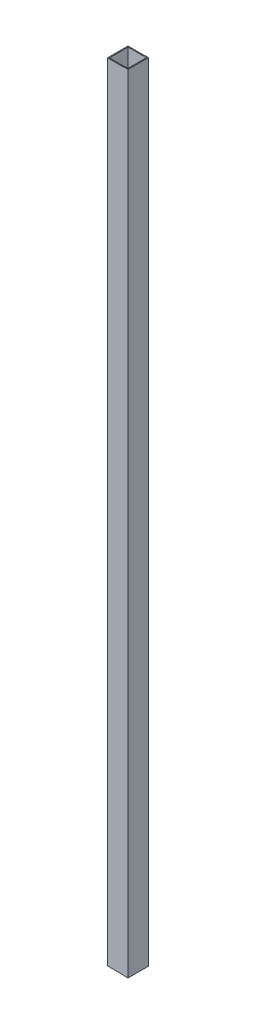
SolidWorks part; units mm, degrees
ref_plane "Front Plane" through (0, 0, 0) normal (0, 0, 1) x (1, 0, 0)
ref_plane "Top Plane" through (0, 0, 0) normal (0, 1, 0) x (1, 0, 0)
ref_plane "Right Plane" through (0, 0, 0) normal (1, 0, 0) x (0, 0, -1)
sketch "Sketch1" plane through (0, 0, 0) normal (0, 1, 0) x (1, 0, 0)
  line L0 (0, 0) -> (0, 50)
  line L1 (0, 50) -> (50, 50)
  line L2 (50, 50) -> (50, 0)
  line L3 (50, 0) -> (0, 0)
  line L4 (2.2, 47.8) -> (47.8, 47.8)
  line L5 (47.8, 47.8) -> (47.8, 2.2)
  line L6 (47.8, 2.2) -> (2.2, 2.2)
  line L7 (2.2, 2.2) -> (2.2, 47.8)
  dimension "D1" = 50
  dimension "D2" = 50
  dimension "D3" = 2.2
extrude "Boss-Extrude1" add sketch "Sketch1" along normal blind 1923
sketch "Sketch2" plane through (0, 0, 0) normal (0, 0, 1) x (1, 0, 0)
  line L0 (0, 0) -> (0, 0.5)
  line L1 (0, 1923) -> (0, 0) construction
  line L2 (0, 0.5) -> (40, 0.5)
  line L3 (40, 0.5) -> (40, 0)
  line L5 (40, 0) -> (0, 0)
  line L6 (0, 1923) -> (40, 1923)
  line L7 (0, 1923) -> (50, 1923) construction
  line L8 (40, 1923) -> (40, 1922.5)
  line L9 (40, 1922.5) -> (0, 1922.5)
  line L10 (0, 1922.5) -> (0, 1923)
  dimension "D1" = 0.5
  dimension "D2" = 40
  dimension "D3" = 0.5
  dimension "D4" = 40
extrude "Cut-Extrude2" cut sketch "Sketch2" against normal blind 50
equation "\"SquareTube_length\"=1923.0"
equation "\"D1@Boss-Extrude1\"=\"SquareTube_length\""
equation "\"SquareTube_inFront1_cutDepth50_R\"=0.5"
equation "\"D1@Sketch2\" = \"SquareTube_inFront3_cutDepth50_R\""
equation "\"SquareTube_inFront1_cutDepth50_L\"=0.5"
equation "\"D3@Sketch2\"= \"SquareTube_inFront3_cutDepth50_L\""
equation "\"CarBeamWidth\"=700.0"
equation "\"MetalSheet_3mm_length\"=5030.0"
equation "\"MetalSheet_3mm_width\"=1923.0"
equation "\"MetalSheet_3mm_FloorCut_L_length\"=1764.0"
equation "\"MetalSheet_3mm_FloorCut_L_disdance\"=1665.0"
equation "\"MetalSheet_3mm_FloorCut_R_length\"=1764.0"
equation "\"MetalSheet_3mm_FloorCut_R_disdance\"=1665.0"
equation "\"indoorHeight\"=1940.0"
equation "\"x\"=66.0"
equation "\"da\"=62.0"
equation "\"SquareTube_wheel_length\"= 750"
equation "\"channelSteel_length\"=5030.0"
equation "\"SquareTube_inFront2_cutDepth50_R\"=0.5"
equation "\"SquareTube_inFront2_cutDepth50_L\"=0.5"
equation "\"SquareTube_inFront3_cutDepth50_R\"=0.5"
equation "\"SquareTube_inFront3_cutDepth50_L\"=0.5"
equation "\"SquareTube_inFront4_cutDepth50_R\"=0.5"
equation "\"SquareTube_inFront4_cutDepth50_L\"=0.5"
equation "\"SquareTube_inFront5_cutDepth50_R\"=50"
equation "\"SquareTube_inFront5_cutDepth50_L\"=50"
equation "\"SquareTube_inFront6_cutDepth50_R\"=50"
equation "\"SquareTube_inFront6_cutDepth50_L\"=50"
equation "\"SquareTube_inFront7_cutDepth50_R\"=50"
equation "\"SquareTube_inFront7_cutDepth50_L\"=50"
equation "\"SquareTube_inFront8_cutDepth50_R\"=50"
equation "\"SquareTube_inFront8_cutDepth50_L\"=50"
equation "\"SquareTube_inFront9_cutDepth50_R\"=50"
equation "\"SquareTube_inFront9_cutDepth50_L\"=50"
equation "\"SquareTube_inFront10_cutDepth50_R\"=50"
equation "\"SquareTube_inFront10_cutDepth50_L\"=50"
equation "\"SquareTube_inBack1_cutDepth50_R\"=50"
equation "\"SquareTube_inBack1_cutDepth50_L\"=50"
equation "\"SquareTube_inBack2_cutDepth50_R\"=50"
equation "\"SquareTube_inBack2_cutDepth50_L\"=50"
equation "\"SquareTube_inBack3_cutDepth50_R\"=50"
equation "\"SquareTube_inBack3_cutDepth50_L\"=50"
equation "\"SquareTube_inBack4_cutDepth50_R\"=50"
equation "\"SquareTube_inBack4_cutDepth50_L\"=50"
equation "\"SquareTube_inBack5_cutDepth50_R\"=50"
equation "\"SquareTube_inBack5_cutDepth50_L\"=50"
equation "\"SquareTube_inBack6_cutDepth50_R\"=0.5"
equation "\"SquareTube_inBack6_cutDepth50_L\"=0.5"
